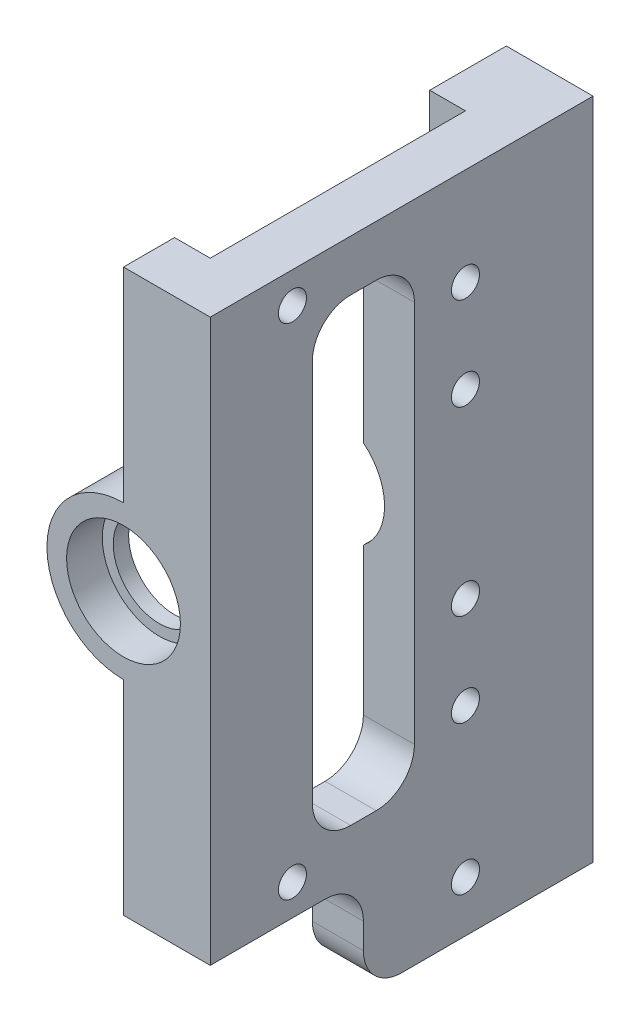
SolidWorks part; units mm, degrees
ref_plane "Front Plane" through (0, 0, 0) normal (0, 0, 1) x (1, 0, 0)
ref_plane "Top Plane" through (0, 0, 0) normal (0, 1, 0) x (1, 0, 0)
ref_plane "Right Plane" through (0, 0, 0) normal (1, 0, 0) x (0, 0, -1)
ref_plane "Plane1" through (0, 0, 0) normal (0, 0, 1) x (1, 0, 0)
sketch "Sketch2" plane through (0, 0, 0) normal (0, 0, 1) x (1, 0, 0)
  circle A0 centre (0, 0) radius 15
  circle A1 centre (0, 0) radius 11.15
  dimension "D1" = 30
  dimension "D2" = 22.3
extrude "Boss-Extrude1" add sketch "Sketch2" against normal up to surface (7 mm away)
sketch "Sketch3" plane through (0, 0, -7) normal (0, 0, -1) x (-1, 0, 0)
  circle A0 centre (0, 0) radius 9
  circle A1 centre (0, 0) radius 15
  dimension "D1" = 18
extrude "Boss-Extrude2" add sketch "Sketch3" along normal blind 3
sketch "Sketch4" plane through (0, 0, 0) normal (0, 0, 1) x (1, 0, 0)
  circle A0 centre (0, 0) radius 11.15 construction
  circle A1 centre (0, 0) radius 15
  circle A2 centre (0, 0) radius 15
  circle A3 centre (0, 0) radius 11.15
  dimension "D1" = 0
extrude "Boss-Extrude3" add sketch "Sketch4" along normal blind 5
sketch "Sketch5" plane through (0, 0, 5) normal (0, 0, 1) x (1, 0, 0)
  line L0 (0, 15) -> (0, 45)
  line L1 (0, -15) -> (0, -45)
  line L2 (17, 15) -> (17, 45)
  line L3 (0, -45) -> (17, -45)
  line L4 (17, -45) -> (17, 15)
  line L5 (17, 45) -> (0, 45)
  circle A0 centre (0, 0) radius 15 construction
  circle A1 centre (0, 0) radius 15
  circle M3 centre (0, 0) radius 15
  dimension "D1" = 30
  dimension "D2" = 30
  dimension "D3" = 17
extrude "Boss-Extrude4" add sketch "Sketch5" against normal blind 8 contours L2 L5 L0 L1 L3 L4 M3
sketch "Sketch7" plane through (0, 0, 5) normal (0, 0, 1) x (1, 0, 0)
  line L0 (17, -45) -> (17, -15)
  line L1 (17, -15) -> (17, 15)
  line L2 (0, 0) -> (-25.0659, 0)
  line L3 (17, 45) -> (17, 15)
  line L4 (7, 45) -> (7, 15)
  line L5 (17, -45) -> (7, -45)
  line L6 (0, -45) -> (17, -45) construction
  line L7 (7, -45) -> (7, -15)
  line L8 (7, -15) -> (17, -15)
  line L9 (17, 15) -> (7, 15)
  line L10 (7, 45) -> (17, 45)
  line L11 (7, 15) -> (7, 8.6789)
  line L12 (7, -15) -> (7, -8.6789)
  circle A0 centre (0, 0) radius 11.15
  line M10 (0, -45) -> (17, -45)
  line M11 (17, -45) -> (17, 45)
  line M12 (17, 45) -> (0, 45)
  circle M14 centre (0, 0) radius 11.15
  dimension "D1" = 30
  dimension "D2" = 10
extrude "Boss-Extrude5" add sketch "Sketch7" along normal blind 20 contours L9 L4 M11 M12 | L12 L8 L9 L11 M11 M14 | L8 L7 M10 M11
sketch "Sketch9" plane through (0, 0, -3) normal (0, 0, -1) x (-1, 0, 0)
  line L5 (-17, 45) -> (-17, -45)
  line L6 (-17, -45) -> (0, -45)
  line L7 (-17, -45) -> (0, -45)
  line L8 (0, 15) -> (0, 45)
  line L9 (0, 45) -> (-17, 45)
  line L10 (-17, 45) -> (-17, -45)
  line L13 (0, 15) -> (0, 45)
  line L14 (0, 45) -> (-17, 45)
  line L15 (0, -45) -> (0, -15)
  line L16 (0, -45) -> (0, -15)
  arc A1 (0, 15) -> (0, -15) centre (0, 0) ccw
  arc A4 (0, 15) -> (0, -15) centre (0, 0) ccw
  dimension "D1" = 0
extrude "Boss-Extrude6" add sketch "Sketch9" along normal up to surface (7 mm away) up to face at (-15, 0, -10)
sketch "Sketch10" plane through (0, 0, 0) normal (-1, 0, 0) x (0, 0, 1)
  line L0 (5, -45) -> (3, -45)
  line L1 (3, -45) -> (3, 45)
  line L2 (-10, 45) -> (5, 45) construction
  line L3 (3, 45) -> (5, 45)
  line L4 (5, 45) -> (5, -45)
  dimension "D1" = 2
extrude "Cut-Extrude1" cut sketch "Sketch10" along normal blind 20
sketch "Sketch12" plane through (7, 0, 0) normal (-1, 0, 0) x (0, 0, 1)
  line L0 (15, 45) -> (15, 26.8394)
  line L1 (25, 45) -> (5, 45) construction
  line L3 (15, 26.8394) -> (25, 26.8394)
  line L4 (25, 45) -> (25, 8.6789) construction
  line L5 (25, 0) -> (30.4607, 0)
  line L6 (25, -8.6789) -> (25, 8.6789) construction
  circle A0 centre (15, 35.9197) radius 2.75
  circle A1 centre (15, 17.7591) radius 2.75
  circle A2 centre (15, -17.7591) radius 2.75
  circle A3 centre (15, -35.9197) radius 2.75
  dimension "D1" = 5.5
extrude "Cut-Extrude2" cut sketch "Sketch12" against normal blind 20 contours A3 | A2 | A1 | L0 A0 | L0 A0
sketch "Sketch13" plane through (0, -45, 0) normal (0, -1, 0) x (1, 0, 0)
  line L6 (7, 5) -> (0, 5)
  line L7 (0, 5) -> (0, -10)
  line L8 (0, -10) -> (17, -10)
  line L9 (17, -10) -> (17, 25)
  line L10 (17, 25) -> (7, 25)
  line L11 (7, 25) -> (7, 5)
  line L12 (7, 5) -> (0, 5)
  line L13 (0, 5) -> (0, -10)
  line L14 (0, -10) -> (17, -10)
  line L15 (17, -10) -> (17, 25)
  line L16 (17, 25) -> (7, 25)
  line L17 (7, 25) -> (7, 5)
  dimension "D1" = 0
extrude "Boss-Extrude7" add sketch "Sketch13" along normal blind 10
sketch "Sketch14" plane through (0, 45, 0) normal (0, 1, 0) x (1, 0, 0)
  line L6 (0, -5) -> (7, -5)
  line L7 (7, -5) -> (7, -25)
  line L8 (7, -25) -> (17, -25)
  line L9 (17, -25) -> (17, 10)
  line L10 (17, 10) -> (0, 10)
  line L11 (0, 10) -> (0, -5)
  line L12 (0, -5) -> (7, -5)
  line L13 (7, -5) -> (7, -25)
  line L14 (7, -25) -> (17, -25)
  line L15 (17, -25) -> (17, 10)
  line L16 (17, 10) -> (0, 10)
  line L17 (0, 10) -> (0, -5)
  dimension "D1" = 0
extrude "Boss-Extrude8" add sketch "Sketch14" along normal blind 10
sketch "Sketch15" plane through (0, 0, 25) normal (0, 0, 1) x (1, 0, 0)
  line L0 (7, 55) -> (7, 8.6789) construction
  line L1 (17, 55) -> (7, 55)
  line L2 (17, 55) -> (17, 45)
  line L3 (17, 45) -> (7, 45)
  line L4 (7, 55) -> (7, 45)
  line L5 (7, -55) -> (7, -8.6789) construction
  line L6 (17, -55) -> (7, -55)
  line L7 (17, -55) -> (17, -45)
  line L8 (17, -45) -> (7, -45)
  line L9 (7, -55) -> (7, -45)
  dimension "D1" = 10
  dimension "D2" = 10
extrude "Boss-Extrude9" add sketch "Sketch15" along normal blind 20
sketch "Sketch16" plane through (0, 0, 45) normal (0, 0, 1) x (1, 0, 0)
  line L4 (17, 45) -> (17, 55)
  line L5 (17, 55) -> (7, 55)
  line L6 (7, 55) -> (7, 45)
  line L7 (7, 45) -> (17, 45)
  line L8 (17, 45) -> (17, 55)
  line L9 (17, 55) -> (7, 55)
  line L10 (7, 55) -> (7, 45)
  line L11 (7, 45) -> (17, 45)
  line L12 (17, -55) -> (17, -45)
  line L13 (17, -45) -> (7, -45)
  line L14 (7, -45) -> (7, -55)
  line L15 (7, -55) -> (17, -55)
  line L16 (17, -55) -> (17, -45)
  line L17 (17, -45) -> (7, -45)
  line L18 (7, -45) -> (7, -55)
  line L19 (7, -55) -> (17, -55)
  dimension "D1" = 0
  dimension "D2" = 0
extrude "Boss-Extrude10" add sketch "Sketch16" along normal blind 10
sketch "Sketch17" plane through (0, -45, 0) normal (0, 1, 0) x (1, 0, 0)
  line L0 (17, -55) -> (7, -55) construction
  line L1 (7, -55) -> (17, -55)
  line L2 (7, -55) -> (7, -45)
  line L3 (7, -45) -> (17, -45)
  line L4 (17, -55) -> (17, -45)
  line L5 (7, -5) -> (7, -55) construction
  line L6 (17, -55) -> (17, 10) construction
  dimension "D1" = 10
extrude "Boss-Extrude11" add sketch "Sketch17" along normal up to surface (90 mm away) up to face at (12, 45, 40)
fillet "Fillet1" radius 7.5 4 edges at (12, -45, 45) (12, -45, 25) (12, 45, 45) (12, 45, 25)
sketch "Sketch18" plane through (0, 0, 55) normal (0, 0, 1) x (1, 0, 0)
  line L2 (0, -15) -> (0, -11.15)
  line L3 (0, 55) -> (0, 11.15)
  line L4 (7, 8.6789) -> (7, 55)
  line L5 (7, 55) -> (0, 55)
  line L6 (0, 55) -> (0, 11.15)
  line L7 (7, 8.6789) -> (7, 55)
  line L8 (7, 55) -> (0, 55)
  line L9 (0, 11.15) -> (0, 15)
  line L10 (0, -15) -> (0, -11.15)
  line L11 (0, 11.15) -> (0, 15)
  line L13 (0, -11.15) -> (0, -55)
  line L14 (0, -55) -> (7, -55)
  line L15 (7, -55) -> (7, -8.6789)
  line L16 (0, -11.15) -> (0, -55)
  line L17 (0, -55) -> (7, -55)
  line L18 (7, -55) -> (7, -8.6789)
  line L20 (7, 55) -> (7, -55)
  line L21 (7, -55) -> (17, -55)
  line L22 (17, -55) -> (17, 55)
  line L23 (17, 55) -> (7, 55)
  line L24 (7, 55) -> (7, -55)
  line L25 (7, -55) -> (17, -55)
  line L26 (17, -55) -> (17, 55)
  line L27 (17, 55) -> (7, 55)
  circle A0 centre (0, 0) radius 11.15
  arc A1 (7, 8.6789) -> (0, 11.15) centre (0, 0) ccw
  arc A2 (7, 8.6789) -> (0, 11.15) centre (0, 0) ccw
  arc A3 (0, -11.15) -> (7, -8.6789) centre (0, 0) ccw
  arc A4 (0, 11.15) -> (0, -11.15) centre (0, 0) ccw
  arc A5 (0, 15) -> (0, -15) centre (0, 0) ccw
  arc A6 (0, 11.15) -> (0, -11.15) centre (0, 0) ccw
  arc A7 (0, 15) -> (0, -15) centre (0, 0) ccw
  arc A8 (0, -11.15) -> (7, -8.6789) centre (0, 0) ccw
  line M17 (7, 55) -> (7, -55)
  line M18 (7, -55) -> (17, -55)
  line M19 (17, -55) -> (17, 55)
  line M20 (17, 55) -> (7, 55)
  dimension "D1" = 0
  dimension "D2" = 0
  dimension "D3" = 0
  dimension "D4" = 0
extrude "Boss-Extrude12" add sketch "Sketch18" along normal blind 10 contours A0 L8 L6 M17 | L6 A7 L10 A0 | A0 L10 L16 L17 M17 | A0 M17 M18 M19 M20
sketch "Sketch19" plane through (0, 0, 55) normal (0, 0, -1) x (-1, 0, 0)
  line L5 (0, 15) -> (0, 55)
  line L6 (0, 55) -> (-17, 55)
  line L7 (-17, 55) -> (-17, -55)
  line L8 (-17, -55) -> (0, -55)
  line L9 (0, -55) -> (0, -15)
  line L10 (0, 15) -> (0, 55)
  line L11 (0, 55) -> (-17, 55)
  line L12 (-17, 55) -> (-17, -55)
  line L13 (-17, -55) -> (0, -55)
  line L14 (0, -55) -> (0, -15)
  circle A0 centre (0, 0) radius 9 construction
  arc A1 (0, -15) -> (0, 15) centre (0, 0) ccw
  arc A2 (0, -15) -> (0, 15) centre (0, 0) ccw
  circle A3 centre (0, 0) radius 9
  dimension "D1" = 0
extrude "Boss-Extrude13" add sketch "Sketch19" against normal blind 3
sketch "Sketch20" plane through (7, 0, 0) normal (-1, 0, 0) x (0, 0, 1)
  line L0 (55, 55) -> (42.8033, 42.8033)
  line L1 (42.8033, -42.8033) -> (55, -55)
  arc A0 (45, 37.5) -> (37.5, 45) centre (37.5, 37.5) ccw construction
  circle A1 centre (48.9017, 48.9017) radius 2.75
  arc A2 (37.5, -45) -> (45, -37.5) centre (37.5, -37.5) ccw construction
  circle A3 centre (48.9017, -48.9017) radius 2.75
  dimension "D1" = 5.5
  dimension "D2" = 5.5
extrude "Cut-Extrude3" cut sketch "Sketch20" against normal through all both and the other way through all contours L1 A3 | L1 A3 | L0 A1 | L0 A1
sketch "Sketch21" plane through (0, -55, 0) normal (0, -1, 0) x (1, 0, 0)
  line L0 (0, -10) -> (0, 5)
  line L1 (0, 5) -> (17, 5)
  line L2 (17, -10) -> (17, 65) construction
  line L4 (0, -10) -> (17, -10)
  line L5 (0, -10) -> (0, 5)
  line L6 (0, 5) -> (17, 5)
  line L7 (17, -10) -> (17, 5)
  line L8 (7, 5) -> (17, 5)
  line L9 (7, 5) -> (7, 15)
  line L10 (7, 15) -> (17, 15)
  line L11 (17, 5) -> (17, 15)
  line M5 (17, -10) -> (17, 65)
  line M10 (7, 5) -> (0, 5)
  line M11 (0, 5) -> (0, -10)
  line M12 (0, -10) -> (17, -10)
  dimension "D1" = 10
extrude "Boss-Extrude14" add sketch "Sketch21" along normal blind 20 contours L1 M10 M11 M12 M5 | L8 L9 L10 L11
sketch "Sketch22" plane through (0, 0, 15) normal (0, 0, 1) x (1, 0, 0)
  line L4 (17, -55) -> (7, -55)
  line L5 (7, -55) -> (7, -75)
  line L6 (7, -75) -> (17, -75)
  line L7 (17, -75) -> (17, -55)
  line L8 (17, -55) -> (7, -55)
  line L9 (7, -55) -> (7, -75)
  line L10 (7, -75) -> (17, -75)
  line L11 (17, -75) -> (17, -55)
  dimension "D1" = 0
extrude "Boss-Extrude15" add sketch "Sketch22" along normal blind 20
fillet "Fillet2" radius 7.5 2 edges at (12, -55, 35) (12, -75, 35)
sketch "Sketch23" plane through (7, 0, 0) normal (-1, 0, 0) x (0, 0, 1)
  line L0 (5, -75) -> (15, -75)
  line L1 (5, -75) -> (27.5, -75) construction
  line L2 (15, -75) -> (15, -65)
  circle A0 centre (15, -65) radius 2.75
  dimension "D3" = 5.5
  dimension "D1" = 10
  dimension "D2" = 10
extrude "Cut-Extrude4" cut sketch "Sketch23" against normal blind 20
